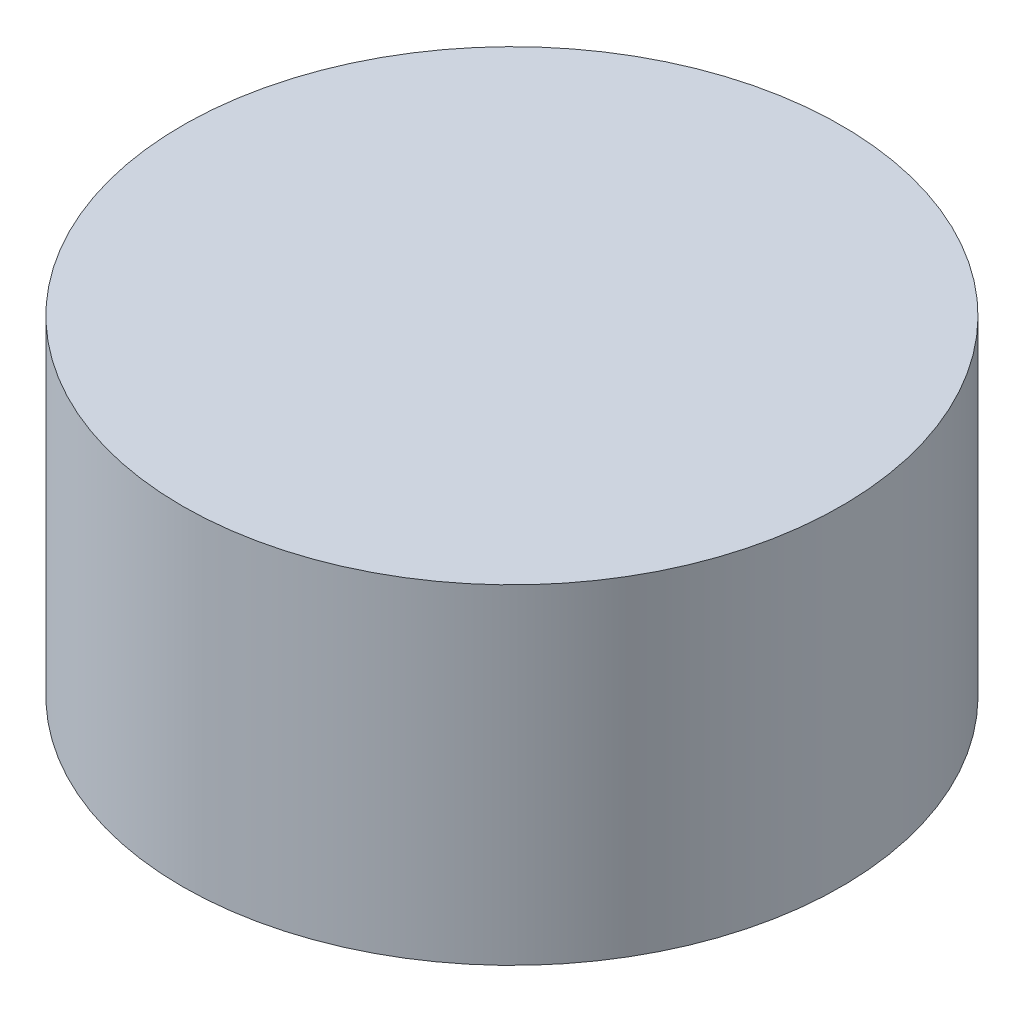
SolidWorks part; units mm, degrees
ref_plane "Front Plane" through (0, 0, 0) normal (0, 0, 1) x (1, 0, 0)
ref_plane "Top Plane" through (0, 0, 0) normal (0, 1, 0) x (1, 0, 0)
ref_plane "Right Plane" through (0, 0, 0) normal (1, 0, 0) x (0, 0, -1)
sketch "Sketch1" plane through (0, 0, 0) normal (0, 1, 0) x (1, 0, 0)
  line L1 (-25, -12.5) -> (25, -12.5)
  line L2 (-25, -12.5) -> (-25, 12.5)
  line L3 (-25, 12.5) -> (25, 12.5)
  line L4 (25, -12.5) -> (25, 12.5)
  line L5 (-25, -12.5) -> (25, 12.5) construction
  line L6 (-25, 12.5) -> (25, -12.5) construction
  point P0 (0, 0)
  point P5 (0, 0)
  point P7 (0, 0)
  point P8 (0, 0)
  point P9 (0, 0)
  point P10 (0, 12.5)
  point P11 (-25, 0)
  point P12 (0, 0)
  point P13 (0, 0)
  dimension "D1" = 25
  dimension "D2" = 50
extrude "Boss-Extrude1" add sketch "Sketch1" along normal blind 25
fillet "Fillet2" radius 5 4 edges at (25, 12.5, -12.5) (25, 12.5, 12.5) (-25, 12.5, 12.5) (-25, 12.5, -12.5)
sketch "Sketch2" plane through (0, 25, 0) normal (0, 1, 0) x (1, 0, 0)
  line L0 (-13.0584, 0) -> (13.06, 0) construction
  line L7 (-13.0584, 9.0342) -> (13.06, 9.0342)
  line L8 (-13.0584, -9.0342) -> (13.06, -9.0342)
  arc A0 (-13.0584, 9.0342) -> (-13.0584, -9.0342) centre (-13.0584, 0) ccw
  arc A1 (13.06, -9.0342) -> (13.06, 9.0342) centre (13.06, 0) ccw
  point P0 (0, 0)
  point P1 (-22.0926, 0)
  point P2 (0, 0)
  point P3 (0, 0)
  point P5 (0.0008, 0)
  dimension "D1" = 26.1184
  dimension "D2" = 9.0342
extrude "Cut-Extrude1" cut sketch "Sketch2" against normal blind 15
sketch "Sketch3" plane through (0, 0, 0) normal (0, 1, 0) x (1, 0, 0)
  circle A0 centre (0, 0) radius 50
  point P3 (0, 0)
  dimension "D1" = 100
extrude "Boss-Extrude2" add sketch "Sketch3" along normal blind 50
sketch "Sketch4" plane through (0, 0, 0) normal (0, -1, 0) x (1, 0, 0)
  circle A0 centre (0, 0) radius 30
  point P3 (0, 0)
  dimension "D1" = 60
extrude "Cut-Extrude2" cut sketch "Sketch4" against normal blind 30
